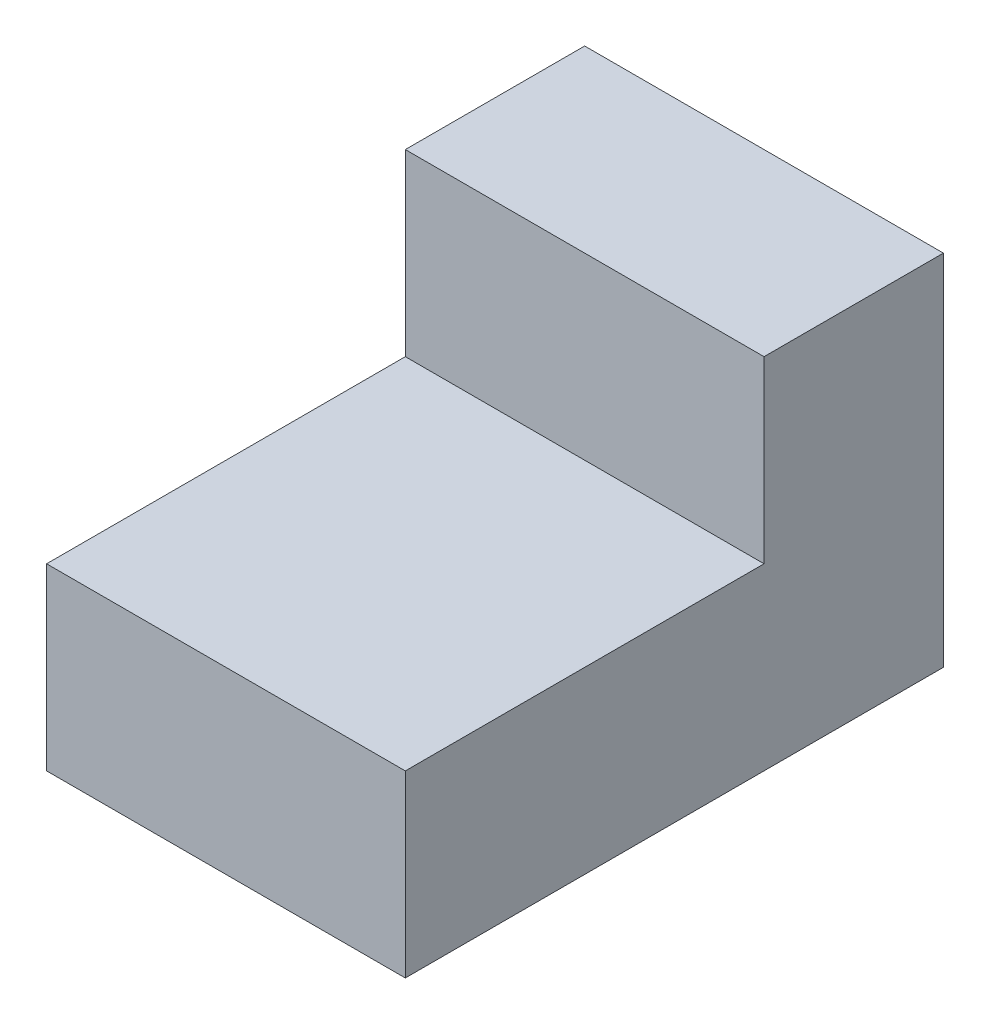
SolidWorks part; units mm, degrees
ref_plane "Front Plane" through (0, 0, 0) normal (0, 0, 1) x (1, 0, 0)
ref_plane "Top Plane" through (0, 0, 0) normal (0, 1, 0) x (1, 0, 0)
ref_plane "Right Plane" through (0, 0, 0) normal (1, 0, 0) x (0, 0, -1)
sketch "Sketch1" plane through (0, 0, 0) normal (0, 1, 0) x (1, 0, 0)
  line L1 (12.7, 19.05) -> (-12.7, 19.05)
  line L2 (12.7, 19.05) -> (12.7, -19.05)
  line L3 (12.7, -19.05) -> (-12.7, -19.05)
  line L4 (-12.7, 19.05) -> (-12.7, -19.05)
  line L5 (12.7, 19.05) -> (-12.7, -19.05) construction
  line L6 (12.7, -19.05) -> (-12.7, 19.05) construction
  point P0 (0, 0)
  dimension "D1" = 25.4
  dimension "D2" = 38.1
extrude "Boss-Extrude1" add sketch "Sketch1" along normal blind 12.7 contours L1 L4 L3 L2
sketch "Sketch2" plane through (0, 12.7, 0) normal (0, 1, 0) x (1, 0, 0)
  line L0 (12.7, 19.05) -> (12.7, -19.05) construction
  line L1 (-12.7, 19.05) -> (12.7, 19.05)
  line L2 (-12.7, 19.05) -> (-12.7, 6.35)
  line L3 (-12.7, 6.35) -> (12.7, 6.35)
  line L4 (12.7, 19.05) -> (12.7, 6.35)
  dimension "D1" = 12.7
extrude "Boss-Extrude2" add sketch "Sketch2" along normal blind 12.7
